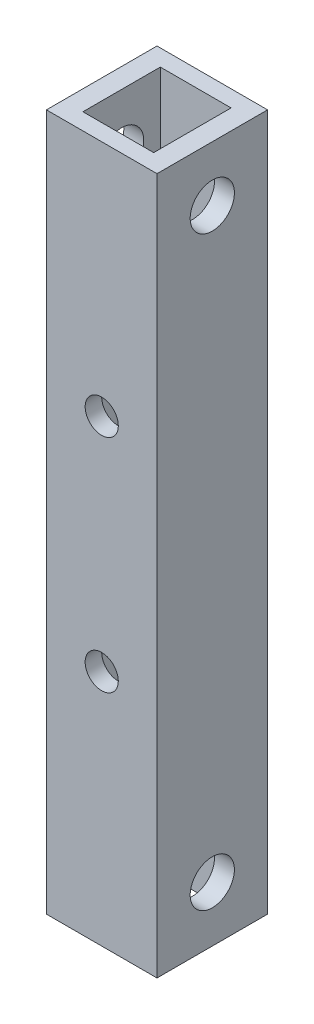
SolidWorks part; units mm, degrees
material "氧化铝"
ref_plane "前视基准面" through (0, 0, 0) normal (0, 0, 1) x (1, 0, 0)
ref_plane "上视基准面" through (0, 0, 0) normal (0, 1, 0) x (1, 0, 0)
ref_plane "右视基准面" through (0, 0, 0) normal (1, 0, 0) x (0, 0, -1)
other "Configuration Table"
sketch "草图1" plane through (0, 0, 0) normal (0, 1, 0) x (1, 0, 0)
  line L1 (-3.2, -3.5) -> (3.2, -3.5)
  line L2 (-3.2, -3.5) -> (-3.2, 3.5)
  line L3 (-3.2, 3.5) -> (3.2, 3.5)
  line L4 (3.2, -3.5) -> (3.2, 3.5)
  line L5 (-3.2, -3.5) -> (3.2, 3.5) construction
  line L6 (-3.2, 3.5) -> (3.2, -3.5) construction
  line L7 (-5, 5) -> (5, 5)
  line L8 (-5, 5) -> (-5, -5)
  line L9 (-5, -5) -> (5, -5)
  line L10 (5, 5) -> (5, -5)
  line L11 (-5, 5) -> (5, -5) construction
  line L12 (-5, -5) -> (5, 5) construction
  point P0 (0, 0)
  point P6 (0, 0)
  dimension "D1" = 1.8
  dimension "D2" = 10
  dimension "D3" = 10
  dimension "D4" = 1.5
extrude "凸台-拉伸1" add sketch "草图1" along normal blind 63
sketch "草图2" plane through (0, 0, 5) normal (0, 0, 1) x (1, 0, 0)
  line L0 (0, 0) -> (0, 63) construction
  line L1 (-5, 0) -> (5, 0) construction
  line L2 (-5, 63) -> (5, 63) construction
  circle A4 centre (0, 41.5) radius 1.5
  circle A5 centre (0, 21.5) radius 1.5
  dimension "D1" = 3
  dimension "D4" = 20
  dimension "D5" = 21.5
extrude "切除-拉伸1" cut sketch "草图2" against normal blind 30
sketch "草图3" plane through (5, 0, 0) normal (1, 0, 0) x (0, 0, -1)
  line L0 (0, 0) -> (0, 63) construction
  line L1 (-5, 63) -> (5, 63) construction
  line L2 (-5, 0) -> (5, 0) construction
  circle A2 centre (0, 5) radius 2
  circle A3 centre (0, 58) radius 2
  dimension "D5" = 4
  dimension "D1" = 5
  dimension "D4" = 5
extrude "切除-拉伸2" cut sketch "草图3" against normal blind 30
